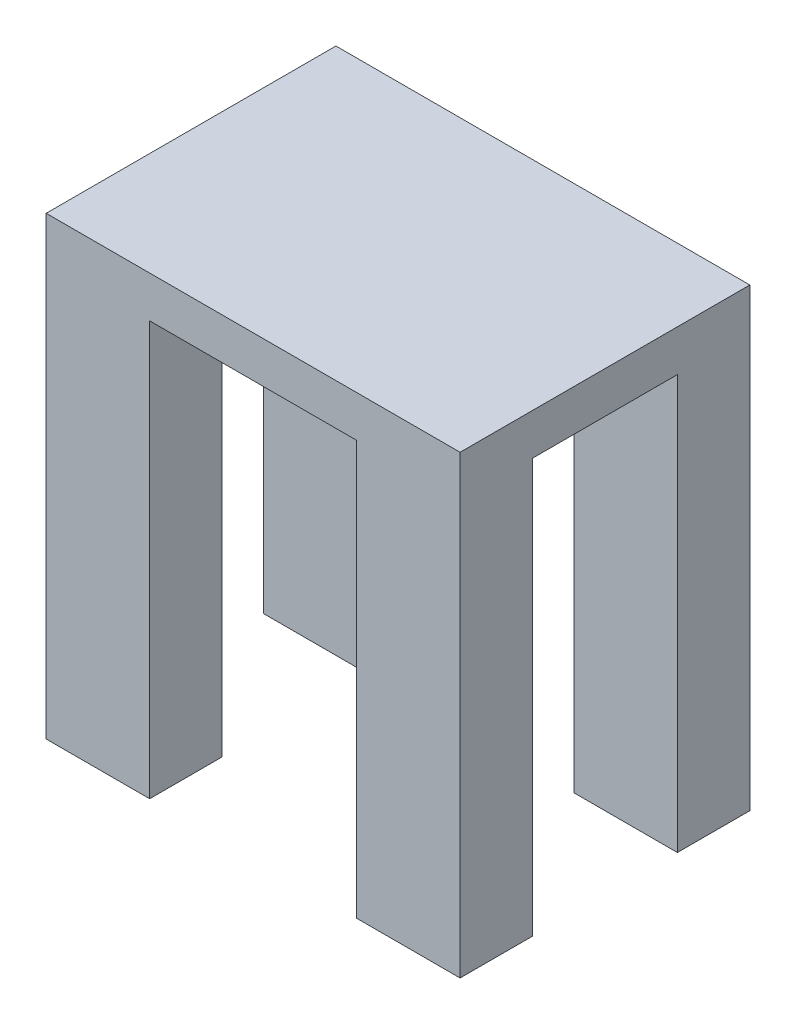
SolidWorks part; units mm, degrees
ref_plane "Alzado" through (0, 0, 0) normal (0, 0, 1) x (1, 0, 0)
ref_plane "Planta" through (0, 0, 0) normal (0, 1, 0) x (1, 0, 0)
ref_plane "Vista lateral" through (0, 0, 0) normal (1, 0, 0) x (0, 0, -1)
sketch "Croquis2" plane through (0, 0, 0) normal (0, 1, 0) x (1, 0, 0)
  line L1 (-250, -175) -> (250, -175)
  line L2 (-250, -175) -> (-250, 175)
  line L3 (-250, 175) -> (250, 175)
  line L4 (250, -175) -> (250, 175)
  line L5 (-250, -175) -> (250, 175) construction
  line L6 (-250, 175) -> (250, -175) construction
  point P0 (0, 0)
  dimension "D1" = 500
  dimension "D2" = 350
extrude "Saliente-Extruir1" add sketch "Croquis2" along normal blind 50
sketch "Croquis3" plane through (0, 0, 0) normal (0, -1, 0) x (1, 0, 0)
  line L0 (-250, 0) -> (250, 0)
  line L1 (-250, -175) -> (-250, 175) construction
  line L2 (250, 175) -> (250, -175) construction
  line L3 (0, 175) -> (0, -175)
  line L4 (-250, 175) -> (250, 175) construction
  line L5 (250, -175) -> (-250, -175) construction
  line L6 (-250, 0) -> (-250, 175)
  line L7 (-250, 175) -> (-250, 87.5)
  line L8 (-250, 87.5) -> (-125, 87.5)
  line L10 (-125, 87.5) -> (-125, 175)
  line L11 (-125, 175) -> (-250, 175)
  line L12 (125, 175) -> (250, 175)
  line L13 (125, 87.5) -> (125, 175)
  line L14 (250, 87.5) -> (125, 87.5)
  line L15 (250, 175) -> (250, 87.5)
  line L16 (125, -87.5) -> (125, -175)
  line L17 (250, -87.5) -> (125, -87.5)
  line L18 (250, -175) -> (250, -87.5)
  line L19 (125, -175) -> (250, -175)
  line L20 (-125, -175) -> (-250, -175)
  line L21 (-125, -87.5) -> (-125, -175)
  line L22 (-250, -87.5) -> (-125, -87.5)
  line L23 (-250, -175) -> (-250, -87.5)
  line M11 (250, -175) -> (250, 175)
  line M12 (250, 175) -> (-250, 175)
  line M13 (-250, 175) -> (-250, -175)
  line M14 (-250, -175) -> (250, -175)
  dimension "D1" = 125
extrude "Saliente-Extruir2" add sketch "Croquis3" along normal blind 500 contours L8 L10 M12 M13 | L22 L21 M13 M14 | L17 L16 M11 M14 | L14 L13 M11 M12
